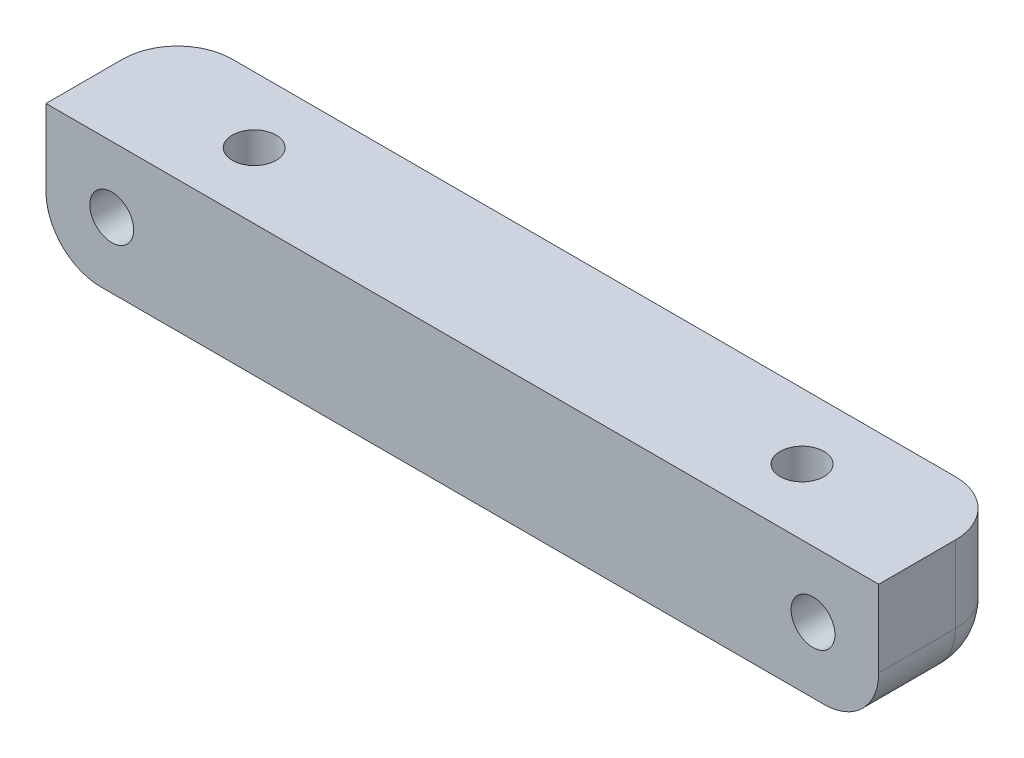
SolidWorks part; units mm, degrees
ref_plane "Front Plane" through (0, 0, 0) normal (0, 0, 1) x (1, 0, 0)
ref_plane "Top Plane" through (0, 0, 0) normal (0, 1, 0) x (1, 0, 0)
ref_plane "Right Plane" through (0, 0, 0) normal (1, 0, 0) x (0, 0, -1)
sketch "Sketch1" plane through (0, 0, 0) normal (0, 0, 1) x (1, 0, 0)
  line L0 (-38, 6) -> (38, -6) construction
  line L1 (-38, 6) -> (38, 6)
  line L2 (-38, 6) -> (-38, -6)
  line L3 (-38, -6) -> (38, -6)
  line L4 (38, 6) -> (38, -6)
  dimension "D1" = 76
  dimension "D2" = 12
extrude "Boss-Extrude1" add sketch "Sketch1" along normal mid plane 12
sketch "Sketch2" plane through (0, 0, 6) normal (0, 0, 1) x (1, 0, 0)
  line L0 (-38, 6) -> (-32, 0) construction
  line L1 (-32, 0) -> (-38, -6) construction
  line L4 (38, -6) -> (32, 0) construction
  line L5 (32, 0) -> (38, 6) construction
  circle A0 centre (-32, 0) radius 2
  circle A1 centre (32, 0) radius 2
  dimension "D1" = 4
extrude "Cut-Extrude1" cut sketch "Sketch2" against normal blind 8.5
sketch "Sketch3" plane through (0, 6, 0) normal (0, 1, 0) x (1, 0, 0)
  line L0 (-25, 0) -> (0, 0) construction
  line L1 (0, 0) -> (25, 0) construction
  circle A0 centre (-25, 0) radius 2
  circle A1 centre (25, 0) radius 2
  dimension "D1" = 4
  dimension "D2" = 25
extrude "Cut-Extrude2" cut sketch "Sketch3" against normal blind 8.5
fillet "Fillet1" radius 5 5 edges at (38, -6, 0) (-38, -6, 0) (-38, 0, -6) (38, 0, -6) (0, -6, -6)
